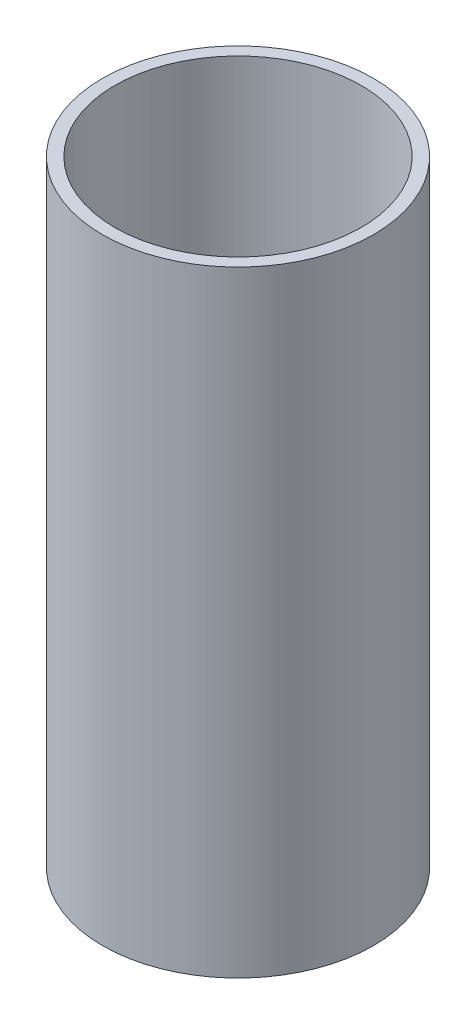
SolidWorks part; units mm, degrees
ref_plane "Front Plane" through (0, 0, 0) normal (0, 0, 1) x (1, 0, 0)
ref_plane "Top Plane" through (0, 0, 0) normal (0, 1, 0) x (1, 0, 0)
ref_plane "Right Plane" through (0, 0, 0) normal (1, 0, 0) x (0, 0, -1)
sketch "Sketch1" plane through (0, 0, 0) normal (0, 1, 0) x (1, 0, 0)
  line L0 (-1000, 0) -> (49000, 0) construction
  line L1 (0, -1000) -> (0, 49000) construction
  line L2 (0, -1000) -> (0, 49000) construction
  line L3 (-1000, 0) -> (49000, 0) construction
  circle A0 centre (0, 0) radius 10
  circle A1 centre (0, 0) radius 11
  dimension "D1" = 20
  dimension "D2" = 22
extrude "Boss-Extrude1" add sketch "Sketch1" along normal blind 50
sketch "Sketch2" plane through (0, 50, 0) normal (0, 1, 0) x (1, 0, 0)
  line L0 (-1000, 0) -> (49000, 0) construction
  line L1 (0, -1000) -> (0, 49000) construction
